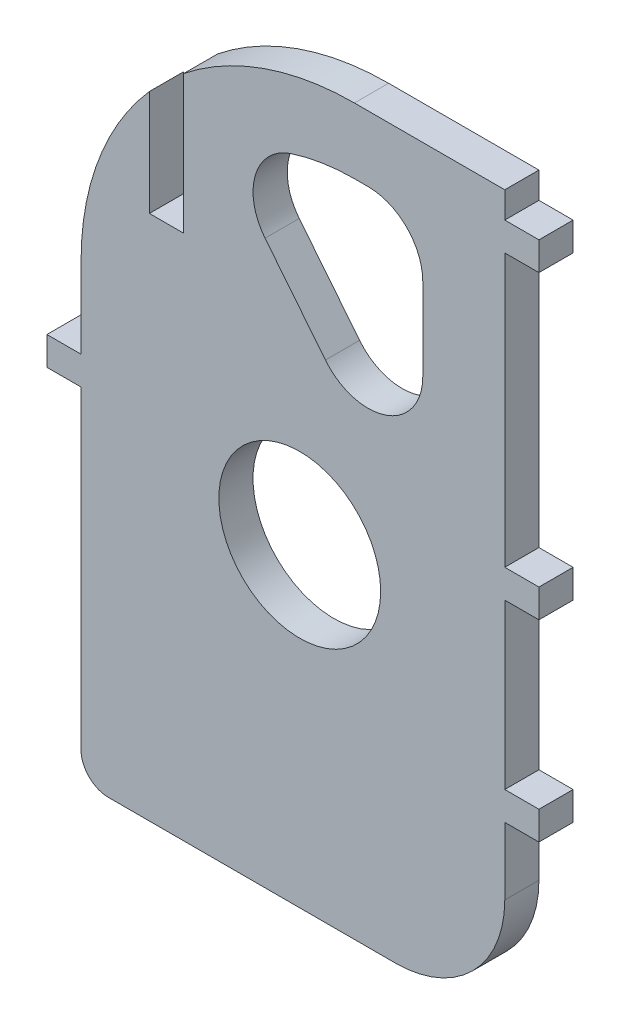
SolidWorks part; units mm, degrees
material "Balsa"
ref_plane "Front Plane" through (0, 0, 0) normal (0, 0, 1) x (1, 0, 0)
ref_plane "Top Plane" through (0, 0, 0) normal (0, 1, 0) x (1, 0, 0)
ref_plane "Right Plane" through (0, 0, 0) normal (1, 0, 0) x (0, 0, -1)
sketch "Sketch1" plane through (0, 0, 0) normal (0, 0, 1) x (1, 0, 0)
  line L0 (0, -1000.1535) -> (0, 48999.8465) construction
  line L2 (-1000, 0) -> (49000, 0) construction
  line L3 (9.525, 16.51) -> (11.1125, 16.51)
  line L4 (2.54, 19.05) -> (9.525, 19.05)
  line L5 (-10.16, 6.35) -> (-10.16, -14.605)
  line L6 (-10.16, -14.605) -> (9.525, -14.605)
  line L7 (9.525, 19.05) -> (9.525, -14.605)
  line L8 (-11.7475, 1.27) -> (-10.16, 1.27)
  line L9 (-11.7475, 1.27) -> (-11.7475, 2.5908)
  line L10 (-11.7475, 2.5908) -> (-10.16, 2.5908)
  line L11 (-10.16, 1.27) -> (-10.16, 2.5908)
  line L12 (9.525, 2.54) -> (11.1125, 2.54)
  line L13 (9.525, 2.54) -> (9.525, 3.8608)
  line L14 (9.525, 3.8608) -> (11.1125, 3.8608)
  line L15 (11.1125, 2.54) -> (11.1125, 3.8608)
  line L16 (9.525, 16.51) -> (9.525, 17.8308)
  line L17 (9.525, 17.8308) -> (11.1125, 17.8308)
  line L18 (11.1125, 16.51) -> (11.1125, 17.8308)
  line L19 (9.525, -5.08) -> (11.1125, -5.08)
  line L20 (9.525, -5.08) -> (9.525, -6.4008)
  line L21 (9.525, -6.4008) -> (11.1125, -6.4008)
  line L22 (11.1125, -5.08) -> (11.1125, -6.4008)
  circle A0 centre (0, 0) radius 3.7592
  arc A3 (2.54, 19.05) -> (-10.16, 6.35) centre (2.54, 6.35) ccw
  dimension "D1" = 7.5184
  dimension "D4" = 14.605
  dimension "D3" = 16.51
  dimension "D5" = 1.5875
  dimension "D9" = 12.7
  dimension "D10" = 1.5875
  dimension "D18" = 1.27
  dimension "D2" = 19.05
  dimension "D6" = 9.525
  dimension "D7" = 1.3208
  dimension "D8" = 19.685
  dimension "D11" = 2.54
  dimension "D12" = 1.3208
  dimension "D13" = 1.3208
  dimension "D14" = 1.5875
  dimension "D19" = 1.5875
  dimension "D20" = 1.3208
  dimension "D21" = 5.08
extrude "Boss-Extrude1" add sketch "Sketch1" along normal blind 1.5875
fillet "Fillet1" radius 5.08 1 edges at (9.525, -14.605, 0.7937)
fillet "Fillet2" radius 1.27 1 edges at (-10.16, -14.605, 0.7937)
sketch "Sketch3" plane through (0, 0, 0) normal (0, 0, -1) x (-1, 0, 0)
  line L0 (-2.54, 19.05) -> (-9.525, 19.05) construction
  line L1 (5.3975, 19.05) -> (6.985, 19.05)
  line L2 (5.3975, 19.05) -> (5.3975, 9.8425)
  line L3 (5.3975, 9.8425) -> (6.985, 9.8425)
  line L4 (6.985, 19.05) -> (6.985, 9.8425)
  line L5 (10.16, 6.35) -> (10.16, 2.5908) construction
  line L6 (10.16, 3.4925) -> (11.7475, 3.4925) construction
  dimension "D1" = 1.5875
  dimension "D2" = 3.175
  dimension "D3" = 6.35
extrude "Cut-Extrude1" cut sketch "Sketch3" against normal through all
sketch "Sketch2" plane through (0, 0, 1.5875) normal (0, 0, 1) x (1, 0, 0)
  line L0 (-3.4925, 13.8846) -> (5.715, 2.3844)
  line L1 (5.715, 16.002) -> (2.54, 16.002)
  line L2 (5.715, 16.002) -> (5.715, 2.3844)
  line L3 (9.525, 16.51) -> (9.525, 3.8608) construction
  arc A2 (2.54, 16.002) -> (-3.4925, 13.8846) centre (2.54, 6.35) ccw
  arc A3 (2.54, 16.002) -> (-3.4925, 13.8846) centre (2.54, 6.35) ccw
  dimension "D2" = 3.81
  dimension "D1" = 3.048
extrude "Weight Reduction" cut sketch "Sketch2" against normal up to next
fillet "Fillet3" radius 2.54 3 edges at (5.715, 2.3844, 0.7937) (-3.4925, 13.8846, 0.7937) (5.715, 16.002, 0.7937)
